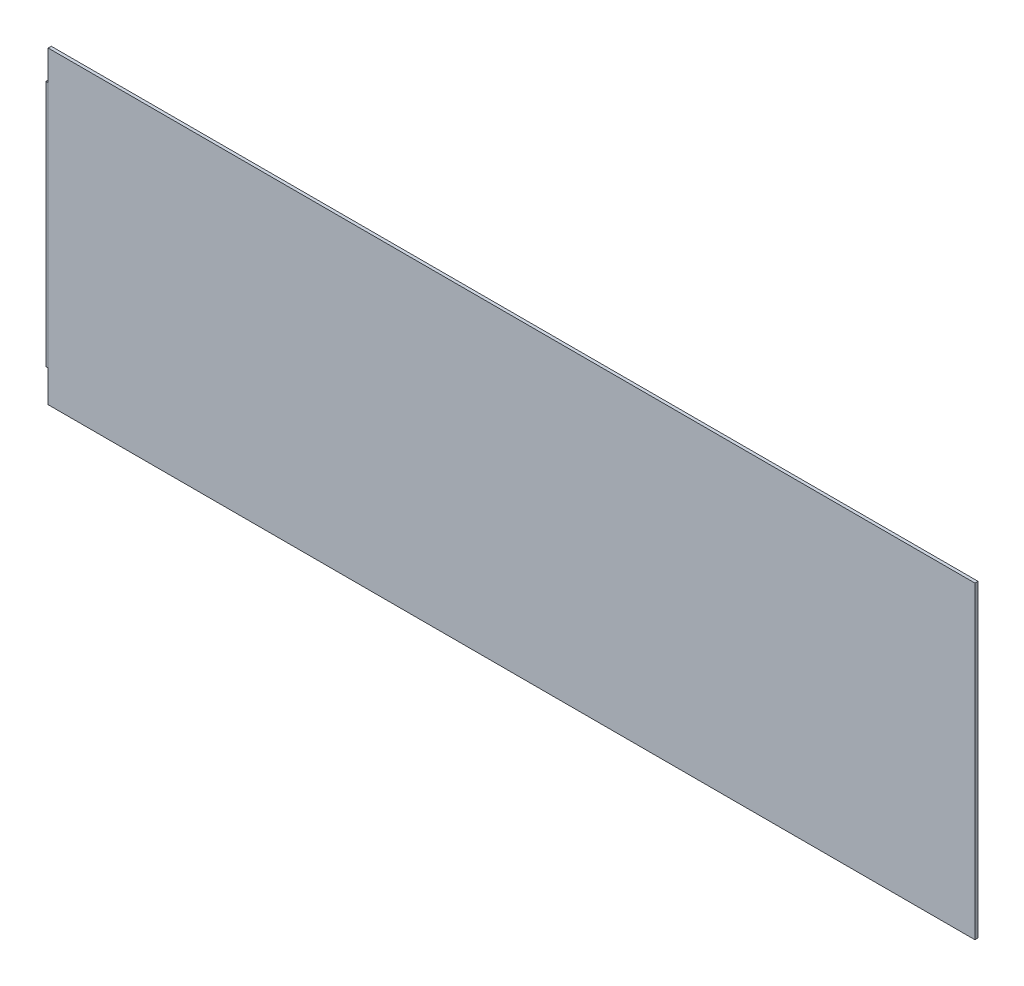
SolidWorks part; units mm, degrees
material "ABS generico"
ref_plane "Piano frontale" through (0, 0, 0) normal (0, 0, 1) x (1, 0, 0)
ref_plane "Piano superiore" through (0, 0, 0) normal (0, 1, 0) x (1, 0, 0)
ref_plane "Piano destro" through (0, 0, 0) normal (1, 0, 0) x (0, 0, -1)
sketch "Schizzo1" plane through (0, 0, 0) normal (0, 0, 1) x (1, 0, 0)
  line L1 (-750, -250) -> (750, -250)
  line L2 (-750, -250) -> (-750, 250)
  line L3 (-750, 250) -> (750, 250)
  line L4 (750, -250) -> (750, 250)
  line L5 (-750, -250) -> (750, 250) construction
  line L6 (-750, 250) -> (750, -250) construction
  point P0 (0, 0)
  dimension "D1" = 500
  dimension "D2" = 1500
extrude "Estrusione-Estrusione1" add sketch "Schizzo1" along normal blind 5
sketch "Schizzo2" plane through (-750, 0, 0) normal (-1, 0, 0) x (0, 0, 1)
  line L0 (2.5, 250) -> (2.5, -250) construction
  line L3 (5, 250) -> (0, 250) construction
  line L8 (5, -250) -> (0, -250) construction
  line L10 (1.5, 200) -> (3.5, 200)
  line L11 (1.5, 200) -> (1.5, -200)
  line L12 (1.5, -200) -> (3.5, -200)
  line L13 (3.5, 200) -> (3.5, -200)
  line L14 (1.5, 200) -> (3.5, -200) construction
  line L15 (1.5, -200) -> (3.5, 200) construction
  point P6 (2.5, 0)
  dimension "D1" = 2
  dimension "D2" = 400
extrude "Estrusione-Estrusione2" add sketch "Schizzo2" along normal blind 5
